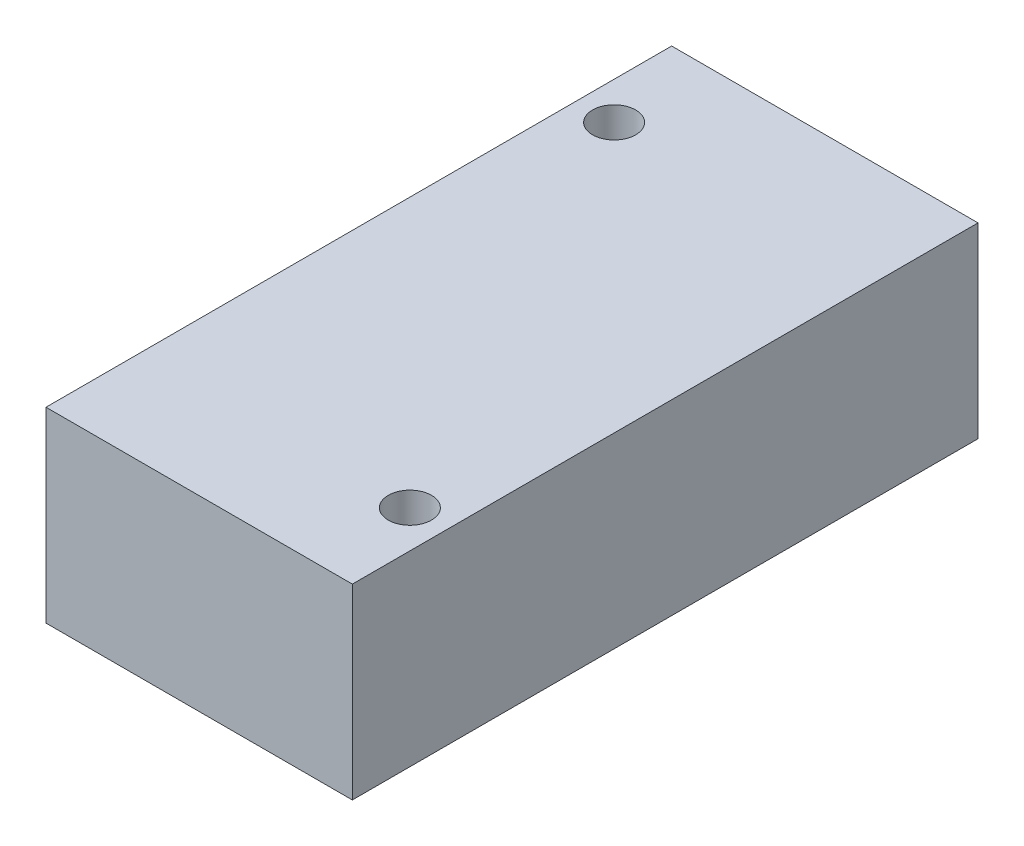
SolidWorks part; units mm, degrees
ref_plane "前视基准面" through (0, 0, 0) normal (0, 0, 1) x (1, 0, 0)
ref_plane "上视基准面" through (0, 0, 0) normal (0, 1, 0) x (1, 0, 0)
ref_plane "右视基准面" through (0, 0, 0) normal (1, 0, 0) x (0, 0, -1)
sketch "草图1" plane through (0, 0, 0) normal (0, 1, 0) x (1, 0, 0)
  line L1 (-10.65, -21.75) -> (10.65, -21.75)
  line L2 (-10.65, -21.75) -> (-10.65, 21.75)
  line L3 (-10.65, 21.75) -> (10.65, 21.75)
  line L4 (10.65, -21.75) -> (10.65, 21.75)
  line L5 (-10.65, -21.75) -> (10.65, 21.75) construction
  line L6 (-10.65, 21.75) -> (10.65, -21.75) construction
  circle A0 centre (-8.05, 15.15) radius 1.5
  circle A1 centre (8.05, -15.15) radius 1.5
  point P0 (0, 0)
  dimension "D3" = 3
  dimension "D4" = 2.6
  dimension "D5" = 6.6
  dimension "D6" = 2.6
  dimension "D7" = 6.6
  dimension "D1" = 21.3
  dimension "D2" = 43.5
extrude "凸台-拉伸1" add sketch "草图1" along normal blind 13
